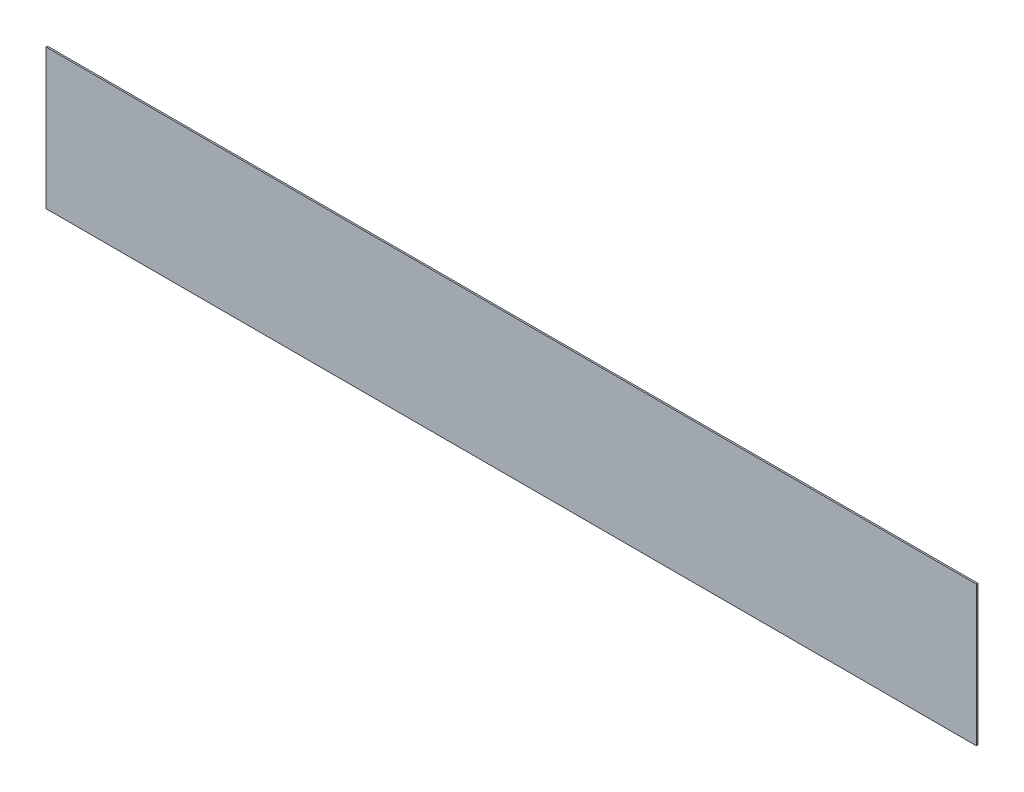
SolidWorks part; units mm, degrees
ref_plane "Front Plane" through (0, 0, 0) normal (0, 0, 1) x (1, 0, 0)
ref_plane "Top Plane" through (0, 0, 0) normal (0, 1, 0) x (1, 0, 0)
ref_plane "Right Plane" through (0, 0, 0) normal (1, 0, 0) x (0, 0, -1)
other "Configuration Table"
sketch "Sketch1" plane through (0, 0, 0) normal (0, 0, 1) x (1, 0, 0)
  line L1 (0, 0) -> (618, 0)
  line L2 (0, 0) -> (0, 93)
  line L3 (0, 93) -> (618, 93)
  line L4 (618, 0) -> (618, 93)
extrude "CEK_taze_on_ic_sac_1.0_1" add sketch "Sketch1" along normal blind 1 separate body
